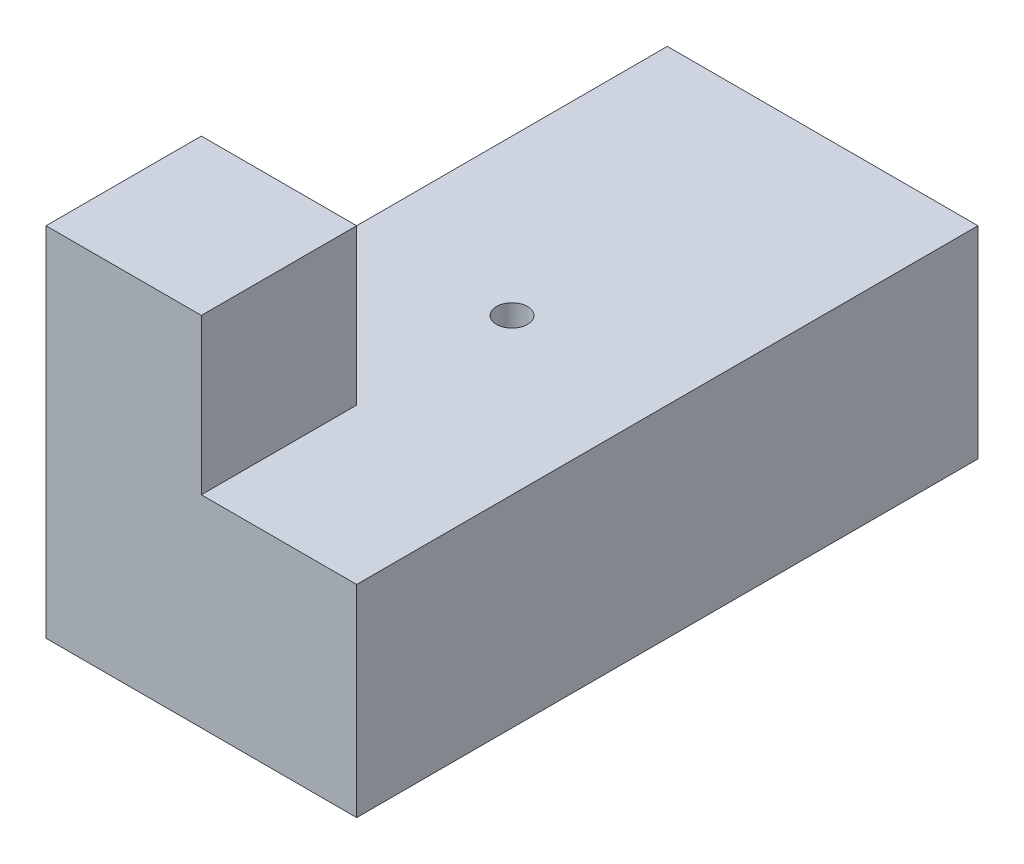
SolidWorks part; units mm, degrees
ref_plane "Front Plane" through (0, 0, 0) normal (0, 0, 1) x (1, 0, 0)
ref_plane "Top Plane" through (0, 0, 0) normal (0, 1, 0) x (1, 0, 0)
ref_plane "Right Plane" through (0, 0, 0) normal (1, 0, 0) x (0, 0, -1)
sketch "Sketch1" plane through (0, 0, 0) normal (0, 1, 0) x (1, 0, 0)
  line L1 (0, 200) -> (100, 200)
  line L2 (0, 200) -> (0, 0)
  line L3 (0, 0) -> (100, 0)
  line L4 (100, 200) -> (100, 0)
  dimension "D1" = 100
  dimension "D2" = 200
extrude "Boss-Extrude1" add sketch "Sketch1" along normal blind 65 contours L4 L1 L2 L3
hole_wizard "Ø10.0mm Dowel Hole1" positions "Sketch2" profile "Sketch4" hole size "Ø10.0" standard "ANSI Metric"
sketch "Sketch2" plane through (0, 65, 0) normal (0, 1, 0) x (1, 0, 0)
  line L0 (0, 0) -> (100, 0) construction
  line L1 (0, 200) -> (0, 0) construction
  point P0 (50, 100)
  dimension "D1" = 100
  dimension "D2" = 50
sketch "Sketch4" plane through (50, 65, -100) normal (1, 0, 0) x (0, 0, 1)
  line L0 (0, 0) -> (0, 43.0043)
  line L1 (0, 43.0043) -> (5, 40)
  line L2 (5, 40) -> (5, 0)
  line L5 (5, 0) -> (0, 0)
  line L10 (0, 43.0043) -> (-5, 40) construction
  line L11 (0, -6.35) -> (0, 107.95) construction
  dimension "Hole Dia." = 10
  dimension "Hole Depth" = 40
  dimension "Drill Angle" = 118
sketch "Sketch5" plane through (0, 65, 0) normal (0, 1, 0) x (1, 0, 0)
  line L0 (0, 0) -> (100, 0) construction
  line L1 (0, 0) -> (50, 0)
  line L2 (0, 0) -> (0, 50)
  line L3 (0, 50) -> (50, 50)
  line L4 (50, 0) -> (50, 50)
  line L5 (0, 200) -> (0, 0) construction
  dimension "D1" = 50
  dimension "D2" = 50
extrude "Boss-Extrude2" add sketch "Sketch5" along normal blind 50
